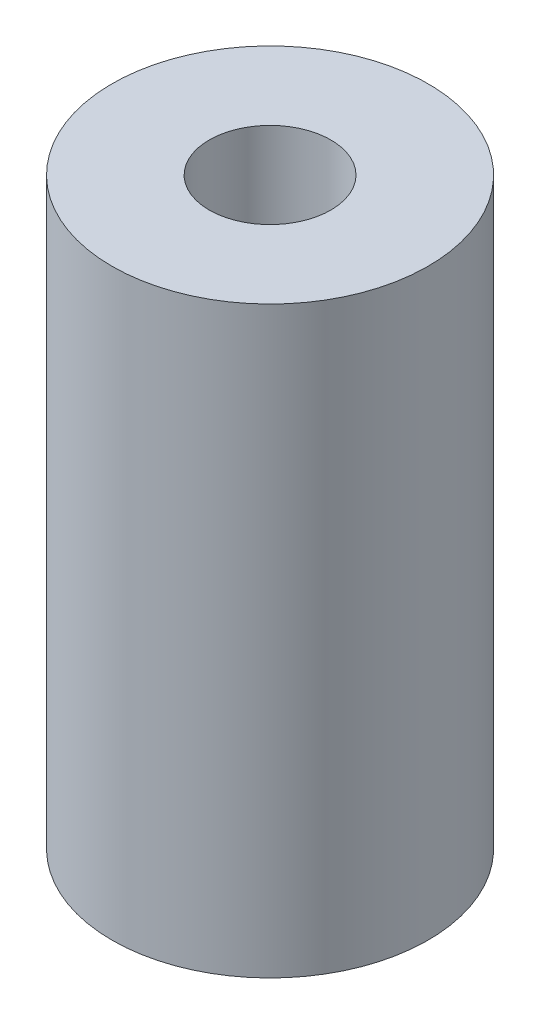
SolidWorks part; units mm, degrees
ref_plane "Front Plane" through (0, 0, 0) normal (0, 0, 1) x (1, 0, 0)
ref_plane "Top Plane" through (0, 0, 0) normal (0, 1, 0) x (1, 0, 0)
ref_plane "Right Plane" through (0, 0, 0) normal (1, 0, 0) x (0, 0, -1)
sketch "Sketch2" plane through (0, 0, 0) normal (0, 1, 0) x (1, 0, 0)
  circle A0 centre (0, 0) radius 1.3
  circle A1 centre (0, 0) radius 0.5
  dimension "D1" = 2.6
  dimension "D2" = 1
extrude "Boss-Extrude1" add sketch "Sketch2" along normal blind 4.8
ref_plane "Plane1" through (0, 2.4, 0) normal (0, 1, 0) x (1, 0, 0)
sketch "Sketch3" plane through (0, 2.4, 0) normal (0, 1, 0) x (1, 0, 0)
  circle A0 centre (0, 0) radius 0.5
  circle A1 centre (0, 0) radius 0.6
  dimension "D1" = 1
  dimension "D2" = 1.2
extrude "Cut-Extrude1" cut sketch "Sketch3" against normal blind 0.05 and the other way blind 0.05
